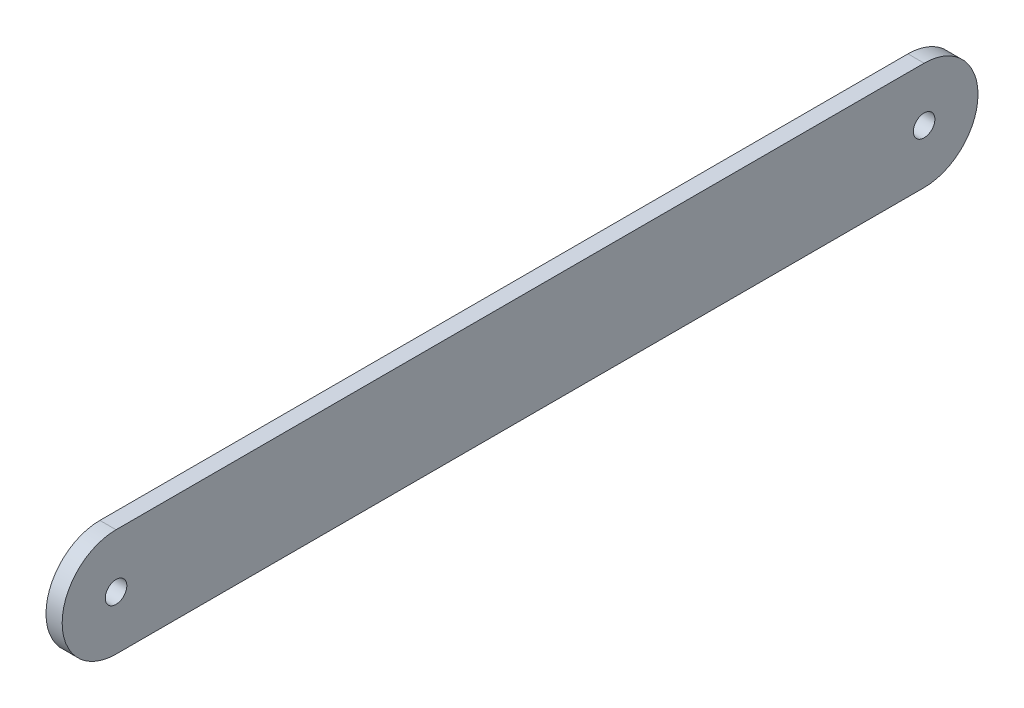
SolidWorks part; units mm, degrees
ref_plane "Front Plane" through (0, 0, 0) normal (0, 0, 1) x (1, 0, 0)
ref_plane "Top Plane" through (0, 0, 0) normal (0, 1, 0) x (1, 0, 0)
ref_plane "Right Plane" through (0, 0, 0) normal (1, 0, 0) x (0, 0, -1)
sketch "Sketch1" plane through (0, 0, 0) normal (1, 0, 0) x (0, 0, -1)
  line L0 (-75, 0) -> (75, 0) construction
  line L1 (-75, 10) -> (75, 10)
  line L2 (-75, -10) -> (75, -10)
  arc A0 (-75, 10) -> (-75, -10) centre (-75, 0) ccw
  arc A1 (75, -10) -> (75, 10) centre (75, 0) ccw
  circle A2 centre (-75, 0) radius 2
  circle A3 centre (75, 0) radius 2
  point P2 (0, 0)
  dimension "D3" = 4
  dimension "D1" = 150
  dimension "D2" = 20
extrude "Boss-Extrude1" add sketch "Sketch1" along normal blind 3
